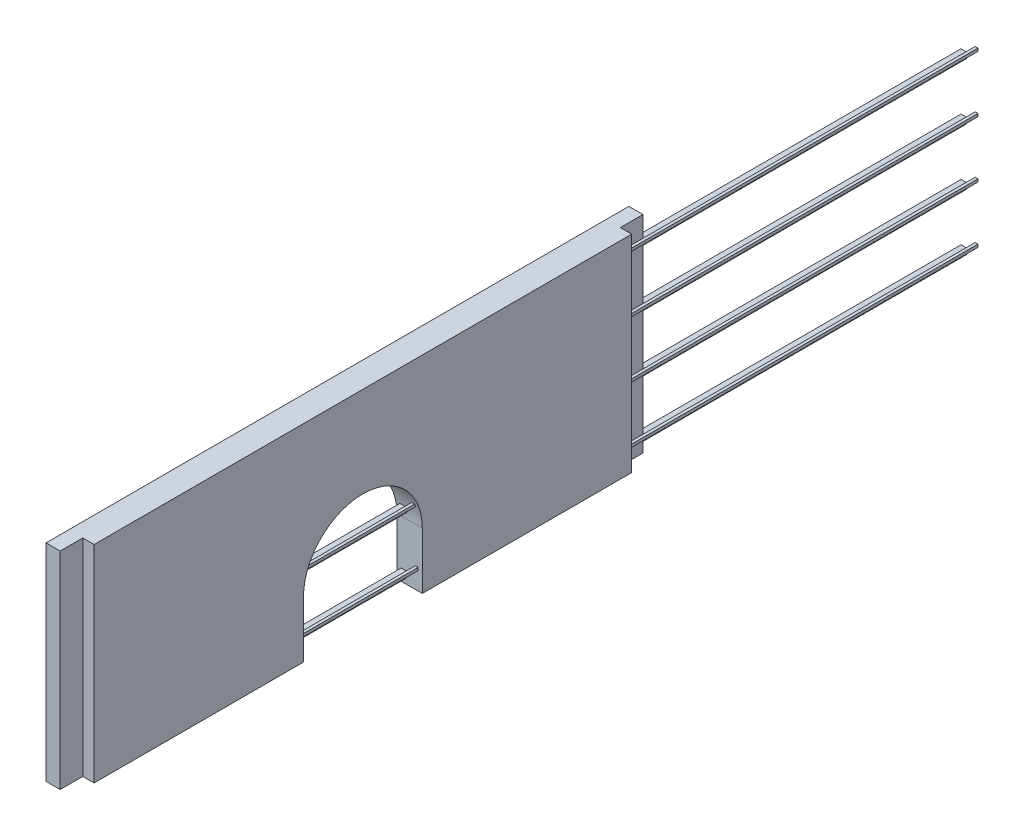
SolidWorks part; units mm, degrees
ref_plane "정면" through (0, 0, 0) normal (0, 0, 1) x (1, 0, 0)
ref_plane "윗면" through (0, 0, 0) normal (0, 1, 0) x (1, 0, 0)
ref_plane "우측면" through (0, 0, 0) normal (1, 0, 0) x (0, 0, -1)
sketch "스케치1" plane through (0, 0, 0) normal (0, 1, 0) x (1, 0, 0)
  line L1 (0, 0) -> (2.5, 0)
  line L2 (0, 0) -> (0, -103)
  line L3 (0, -103) -> (2.5, -103)
  line L4 (2.5, 0) -> (2.5, -103)
  line L5 (2.5, -4) -> (4.5, -4)
  line L6 (2.5, -4) -> (2.5, -99)
  line L7 (2.5, -99) -> (4.5, -99)
  line L8 (4.5, -4) -> (4.5, -99)
  dimension "D1" = 103
  dimension "D2" = 2.5
  dimension "D3" = 95
  dimension "D4" = 4
extrude "보스-돌출1" add sketch "스케치1" along normal blind 99.5 contours L4 L1 L2 L3 | L8 L5 L4 L7
sketch "스케치2" plane through (4.5, 0, 0) normal (1, 0, 0) x (0, 0, -1)
  line L0 (-4, 0) -> (-99, 0) construction
  line L1 (-51.5, 0) -> (-51.5, 17.427) construction
  line L2 (-62, 10) -> (-62, 0)
  line L3 (-41, 10) -> (-41, 0)
  line L4 (-62, 0) -> (-41, 0)
  arc A0 (-41, 10) -> (-62, 10) centre (-51.5, 10) ccw
  dimension "D1" = 21
  dimension "D2" = 10
extrude "컷-돌출2" cut sketch "스케치2" against normal up to surface (4.5 mm away) up to face at (0, 49.75, 51.5)
sketch "스케치3" plane through (0, 99.5, 0) normal (0, 1, 0) x (1, 0, 0)
  line L8 (2.5, -4) -> (2.5, 0)
  line L9 (2.5, 0) -> (0, 0)
  line L10 (0, 0) -> (0, -103)
  line L11 (0, -103) -> (2.5, -103)
  line L12 (2.5, -103) -> (2.5, -99)
  line L13 (2.5, -99) -> (4.5, -99)
  line L14 (4.5, -99) -> (4.5, -4)
  line L15 (4.5, -4) -> (2.5, -4)
  line L16 (2.5, -4) -> (2.5, 0)
  line L17 (2.5, 0) -> (0, 0)
  line L18 (0, 0) -> (0, -103)
  line L19 (0, -103) -> (2.5, -103)
  line L20 (2.5, -103) -> (2.5, -99)
  line L21 (2.5, -99) -> (4.5, -99)
  line L22 (4.5, -99) -> (4.5, -4)
  line L23 (4.5, -4) -> (2.5, -4)
  dimension "D1" = 0
extrude "컷-돌출3" cut sketch "스케치3" against normal blind 58.5
sketch "스케치4" plane through (0, 41, 0) normal (0, 1, 0) x (1, 0, 0)
  line L8 (4.5, -4) -> (2.5, -4)
  line L9 (2.5, -4) -> (2.5, 0)
  line L10 (2.5, 0) -> (0, 0)
  line L11 (0, 0) -> (0, -103)
  line L12 (0, -103) -> (2.5, -103)
  line L13 (2.5, -103) -> (2.5, -99)
  line L14 (2.5, -99) -> (4.5, -99)
  line L15 (4.5, -99) -> (4.5, -4)
  line L16 (4.5, -4) -> (2.5, -4)
  line L17 (2.5, -4) -> (2.5, 0)
  line L18 (2.5, 0) -> (0, 0)
  line L19 (0, 0) -> (0, -103)
  line L20 (0, -103) -> (2.5, -103)
  line L21 (2.5, -103) -> (2.5, -99)
  line L22 (2.5, -99) -> (4.5, -99)
  line L23 (4.5, -99) -> (4.5, -4)
  dimension "D1" = 0
extrude "컷-돌출4" cut sketch "스케치4" against normal blind 4.5
sketch "스케치5" plane through (0, 36.5, 0) normal (0, 1, 0) x (1, 0, 0)
  line L8 (4.5, -99) -> (4.5, -4)
  line L9 (4.5, -4) -> (2.5, -4)
  line L10 (2.5, -4) -> (2.5, 0)
  line L11 (2.5, 0) -> (0, 0)
  line L12 (0, 0) -> (0, -103)
  line L13 (0, -103) -> (2.5, -103)
  line L14 (2.5, -103) -> (2.5, -99)
  line L15 (2.5, -99) -> (4.5, -99)
  line L16 (4.5, -99) -> (4.5, -4)
  line L17 (4.5, -4) -> (2.5, -4)
  line L18 (2.5, -4) -> (2.5, 0)
  line L19 (2.5, 0) -> (0, 0)
  line L20 (0, 0) -> (0, -103)
  line L21 (0, -103) -> (2.5, -103)
  line L22 (2.5, -103) -> (2.5, -99)
  line L23 (2.5, -99) -> (4.5, -99)
  dimension "D1" = 0
sketch "스케치6" plane through (0, 0, 0) normal (0, -1, 0) x (1, 0, 0)
  line L0 (0, 62) -> (0, 103) construction
  line L1 (0, 82.5) -> (1.6, 82.5)
  line L2 (0, 82.5) -> (0, 65.5)
  line L3 (0, 65.5) -> (1.6, 65.5)
  line L4 (1.6, 82.5) -> (1.6, 65.5)
extrude "컷-돌출5" cut sketch "스케치6" against normal blind 10
sketch "스케치7" plane through (0, 0, 0) normal (0, 0, -1) x (-1, 0, 0)
  line L0 (0, 36.5) -> (0, 0) construction
  line L1 (-1.75, 1.0246) -> (-0.75, 1.0246)
  line L2 (-1.75, 1.0246) -> (-1.75, 2.0246)
  line L3 (-1.75, 2.0246) -> (-0.75, 2.0246)
  line L4 (-0.75, 1.0246) -> (-0.75, 2.0246)
  line L9 (-1.75, 11.0246) -> (-0.75, 11.0246)
  line L10 (-1.75, 11.0246) -> (-1.75, 12.0246)
  line L11 (-1.75, 12.0246) -> (-0.75, 12.0246)
  line L12 (-0.75, 11.0246) -> (-0.75, 12.0246)
  line L13 (-1.75, 21.0246) -> (-0.75, 21.0246)
  line L14 (-1.75, 21.0246) -> (-1.75, 22.0246)
  line L15 (-1.75, 22.0246) -> (-0.75, 22.0246)
  line L16 (-0.75, 21.0246) -> (-0.75, 22.0246)
  line L17 (-1.75, 31.0246) -> (-0.75, 31.0246)
  line L18 (-1.75, 31.0246) -> (-1.75, 32.0246)
  line L19 (-1.75, 32.0246) -> (-0.75, 32.0246)
  line L20 (-0.75, 31.0246) -> (-0.75, 32.0246)
  dimension "D1" = 1
  dimension "D2" = 1
  dimension "D3" = 0.75
  dimension "D4" = 4
extrude "보스-돌출2" add sketch "스케치7" along normal up to surface and the other way up to surface
sketch "스케치8" plane through (0, 0, 4) normal (0, 0, -1) x (-1, 0, 0)
  line L0 (-4.5, 36.5) -> (-4.5, 0) construction
  line L1 (-3.75, 3.1186) -> (-3.25, 3.1186)
  line L2 (-3.75, 3.1186) -> (-3.75, 3.6186)
  line L3 (-3.75, 3.6186) -> (-3.25, 3.6186)
  line L4 (-3.25, 3.1186) -> (-3.25, 3.6186)
  line L5 (-3.75, 13.1186) -> (-3.25, 13.1186)
  line L6 (-3.75, 13.1186) -> (-3.75, 13.6186)
  line L7 (-3.75, 13.6186) -> (-3.25, 13.6186)
  line L8 (-3.25, 13.1186) -> (-3.25, 13.6186)
  line L9 (-3.75, 23.1186) -> (-3.25, 23.1186)
  line L10 (-3.75, 23.1186) -> (-3.75, 23.6186)
  line L11 (-3.75, 23.6186) -> (-3.25, 23.6186)
  line L12 (-3.25, 23.1186) -> (-3.25, 23.6186)
  line L13 (-3.75, 33.1186) -> (-3.25, 33.1186)
  line L14 (-3.75, 33.1186) -> (-3.75, 33.6186)
  line L15 (-3.75, 33.6186) -> (-3.25, 33.6186)
  line L16 (-3.25, 33.1186) -> (-3.25, 33.6186)
  dimension "D1" = 0.5
  dimension "D2" = 0.5
  dimension "D3" = 0.75
  dimension "D4" = 4
extrude "보스-돌출3" add sketch "스케치8" along normal up to surface and the other way up to surface
